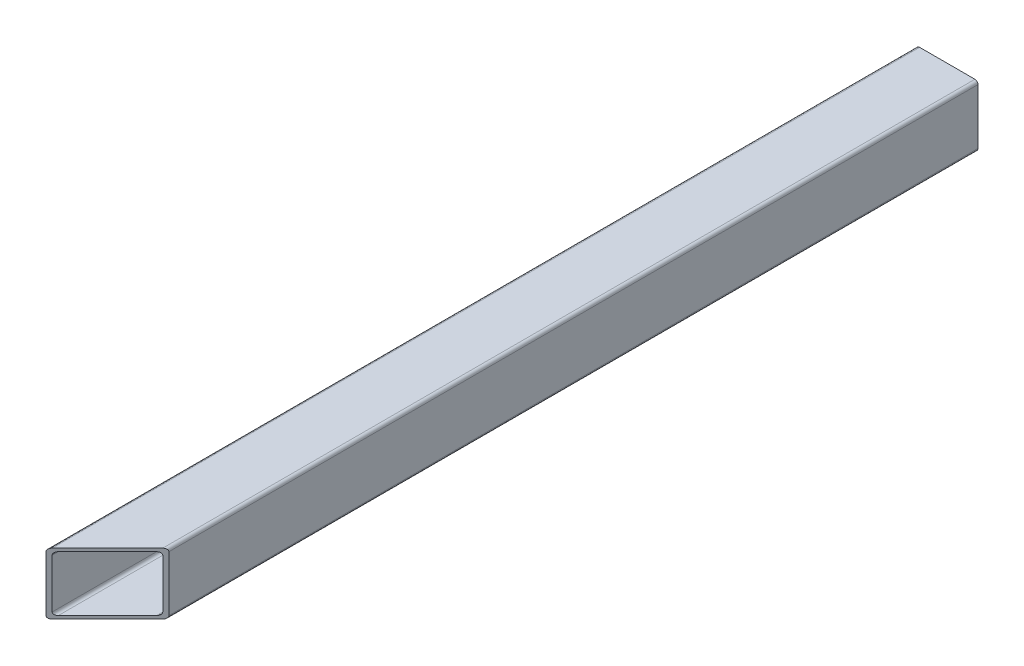
SolidWorks part; units mm, degrees
ref_plane "Płaszczyzna przednia" through (0, 0, 0) normal (0, 0, 1) x (1, 0, 0)
ref_plane "Płaszczyzna górna" through (0, 0, 0) normal (0, 1, 0) x (1, 0, 0)
ref_plane "Płaszczyzna prawa" through (0, 0, 0) normal (1, 0, 0) x (0, 0, -1)
sketch "Szkic2" plane through (0, 0, 0) normal (0, 0, 1) x (1, 0, 0)
  line L0 (3, 6) -> (3, 54)
  line L1 (3, 0) -> (57, 0)
  line L2 (0, 3) -> (0, 57)
  line L3 (3, 60) -> (57, 60)
  line L4 (60, 3) -> (60, 57)
  line L5 (0, 0) -> (42.6554, 0)
  line L6 (0, 0) -> (0, 31.4913)
  line L7 (6, 57) -> (54, 57)
  line L8 (57, 6) -> (57, 54)
  line L9 (6, 3) -> (54, 3)
  line L10 (0, 60) -> (60, 60) construction
  line L11 (60, 0) -> (60, 60) construction
  line L12 (3, 57) -> (57, 57) construction
  line L13 (57, 3) -> (57, 57) construction
  line L14 (0, 0) -> (60, 0) construction
  line L15 (3, 3) -> (57, 3) construction
  line L16 (3, 3) -> (3, 57) construction
  line L17 (0, 0) -> (0, 60) construction
  arc A0 (57, 60) -> (60, 57) centre (57, 57) cw
  arc A1 (54, 57) -> (57, 54) centre (54, 54) cw
  arc A2 (57, 0) -> (60, 3) centre (57, 3) ccw
  arc A3 (57, 6) -> (54, 3) centre (54, 6) cw
  arc A4 (3, 6) -> (6, 3) centre (6, 6) ccw
  arc A5 (3, 0) -> (0, 3) centre (3, 3) cw
  arc A6 (3, 54) -> (6, 57) centre (6, 54) cw
  arc A7 (0, 57) -> (3, 60) centre (3, 57) cw
  point P14 (60, 60)
  dimension "D4" = 3
  dimension "D3" = 3
extrude "Dodanie-wyciągnięcie1" add sketch "Szkic2" along normal blind 850 contours A7 L2 A5 L1 A2 L4 A0 L3 L0 A6 L7 A1 L8 A3 L9 A4
ref_plane "Płaszczyzna1" through (425, 0, 425) normal (0.7071, 0, 0.7071) x (0, 1, 0)
sketch "Szkic3" plane through (425, 0, 425) normal (0.7071, 0, 0.7071) x (0, 1, 0)
  line L1 (-54.7807, 632.7586) -> (128.6679, 632.7586)
  line L2 (-54.7807, 632.7586) -> (-54.7807, 514.0755)
  line L3 (-54.7807, 514.0755) -> (128.6679, 514.0755)
  line L4 (128.6679, 632.7586) -> (128.6679, 514.0755)
extrude "Wytnij-wyciągnięcie1" cut sketch "Szkic3" along normal through all
